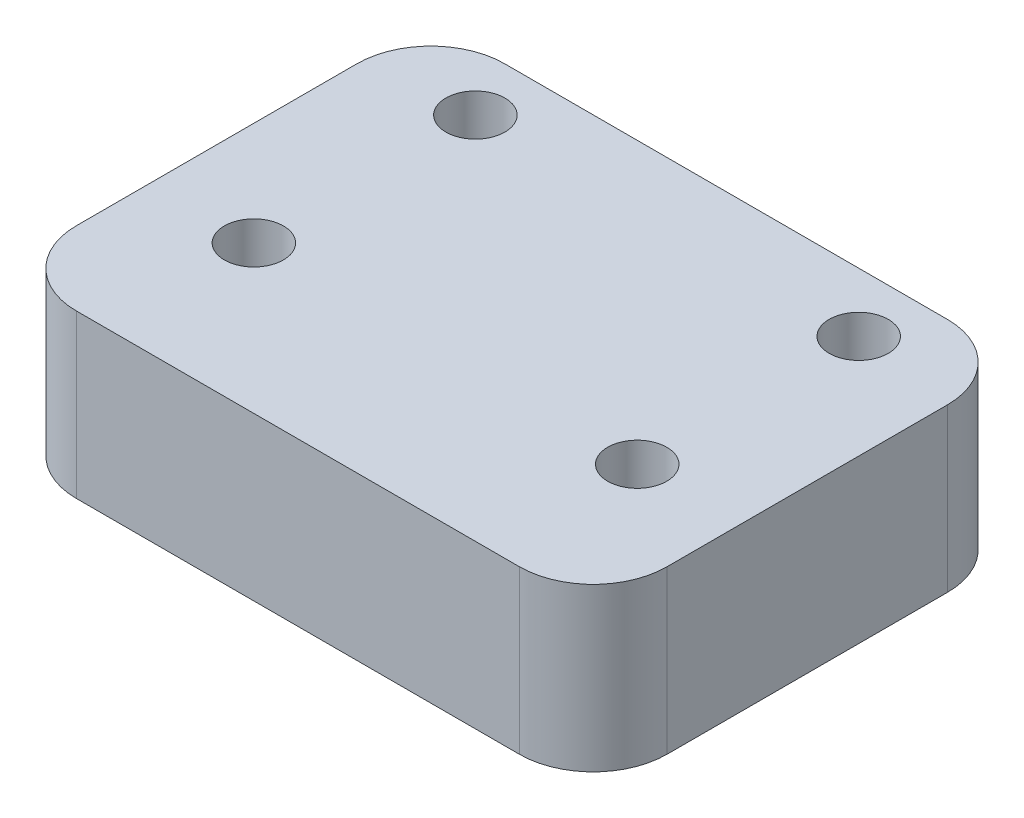
SolidWorks part; units mm, degrees
ref_plane "前基準面" through (0, 0, 0) normal (0, 0, 1) x (1, 0, 0)
ref_plane "上基準面" through (0, 0, 0) normal (0, 1, 0) x (1, 0, 0)
ref_plane "右基準面" through (0, 0, 0) normal (1, 0, 0) x (0, 0, -1)
sketch "草圖1" plane through (0, 0, 0) normal (0, 1, 0) x (1, 0, 0)
  line L0 (-12.98, 10.5) -> (12.98, 10.5) construction
  line L1 (-20, 14.5) -> (20, 14.5)
  line L2 (-20, 14.5) -> (-20, -14.5)
  line L3 (-20, -14.5) -> (20, -14.5)
  line L4 (20, 14.5) -> (20, -14.5)
  line L5 (-20, 14.5) -> (20, -14.5) construction
  line L6 (-20, -14.5) -> (20, 14.5) construction
  circle A0 centre (12.98, 10.5) radius 2
  circle A1 centre (-12.98, 10.5) radius 2
  circle A2 centre (-12.98, -4.5) radius 2
  circle A3 centre (12.98, -4.5) radius 2
  point P0 (0, 0)
  point P14 (0, 10.5)
  dimension "D4" = 4
  dimension "D1" = 29
  dimension "D2" = 40
  dimension "D3" = 10
  dimension "D5" = 25.96
  dimension "D6" = 15
extrude "填料-伸長1" add sketch "草圖1" along normal blind 11
fillet "圓角1" radius 5 4 edges at (-20, 5.5, 14.5) (20, 5.5, 14.5) (-20, 5.5, -14.5) (20, 5.5, -14.5)
